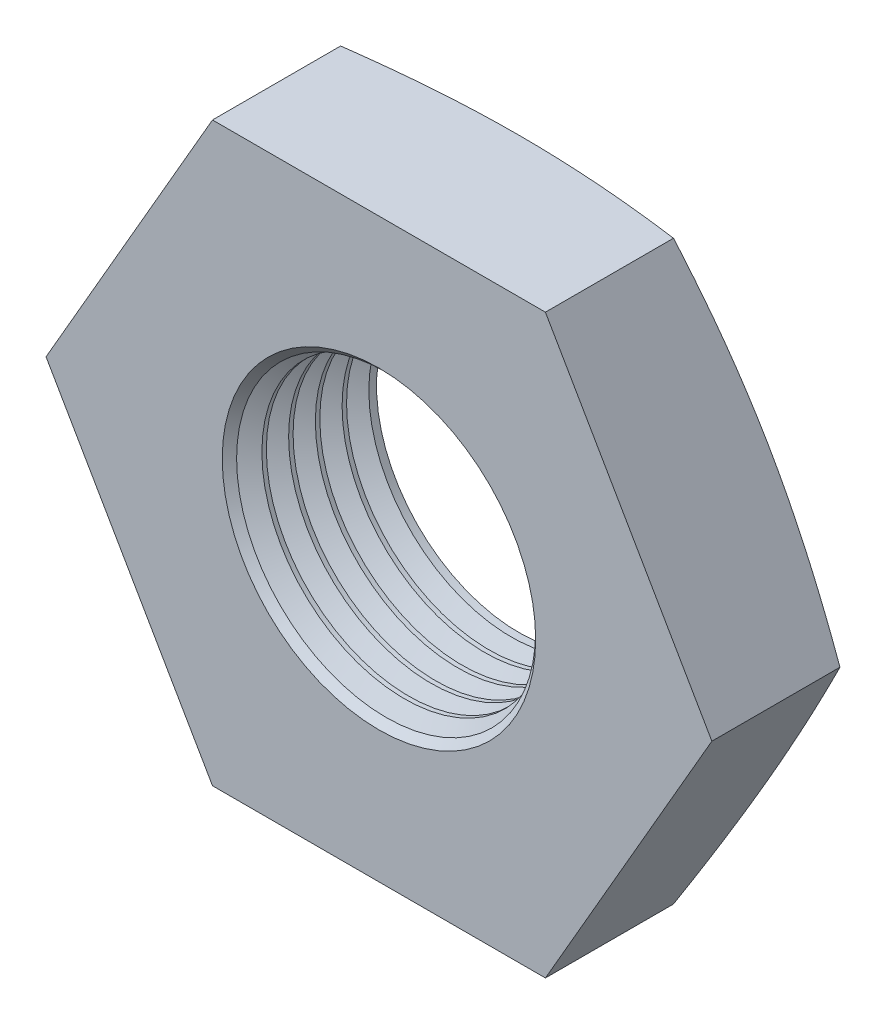
SolidWorks part; units mm, degrees
ref_plane "Front" through (0, 0, 0) normal (0, 0, 1) x (1, 0, 0)
ref_plane "Top" through (0, 0, 0) normal (0, 1, 0) x (1, 0, 0)
ref_plane "Right" through (0, 0, 0) normal (1, 0, 0) x (0, 0, -1)
sketch "Sketch1" plane through (0, 0, 0) normal (0, 0, 1) x (1, 0, 0)
  line L1 (2.0207, -3.5) -> (4.0415, 0)
  line L2 (4.0415, 0) -> (2.0207, 3.5)
  line L3 (2.0207, 3.5) -> (-2.0207, 3.5)
  line L4 (-2.0207, 3.5) -> (-4.0415, 0)
  line L5 (-4.0415, 0) -> (-2.0207, -3.5)
  line L6 (-2.0207, -3.5) -> (2.0207, -3.5)
  circle A0 centre (0, 0) radius 3.5 construction
  circle A1 centre (0, 0) radius 1.7295
  dimension "D" = 3.459
  dimension "s" = 7
  dimension "e" = 8.0829
extrude "BaseNut" add sketch "Sketch1" against normal blind 1.7
cosmetic thread "ThreadCosmetic1" [suppressed] parameters "D2"=4
sketch "Sketch2" plane through (0, 0, 0) normal (0, 1, 0) x (1, 0, 0)
  line L0 (-4.0415, 1.7) -> (-3.5, 1.7)
  line L2 (-3.5, 1.7) -> (-4.0415, 1.5549)
  line L3 (-4.0415, 1.5549) -> (-4.0415, 1.7)
  line L4 (0, 3.3759) -> (0, -9.8171) construction
  line L6 (-9.7712, 0.85) -> (9.8853, 0.85) construction
  dimension "dw" = 7
  dimension "Angle" = 15
  dimension "D2" = 0.85
revolve "Double-Chamfer" cut sketch "Sketch2" angle 360 about L4
chamfer "Chamfer1" distance 0.1729 angle 45 1 edges at (1.7295, 0, 0)
sketch "Sketch3" plane through (0, 0, 0) normal (0, 1, 0) x (1, 0, 0)
  line L0 (0, 2.7394) -> (0, -0.894) construction
  line L1 (1.459, 0.3082) -> (1.7295, 0.3082)
  line L2 (1.7295, 0.3082) -> (1.9638, 0.1729)
  line L3 (1.9638, 0.1729) -> (1.7295, 0.0377)
  line L4 (1.7295, 0.0377) -> (1.459, 0.0377)
  line L5 (1.459, 0.0377) -> (1.459, 0.3082)
  line L6 (1.7295, 0.1729) -> (-1.7295, 0.1729) construction
  dimension "D1" = 0.2705
  dimension "D2" = 3.459
revolve "Cut-Revolve10" cut sketch "Sketch3" angle 360 about L0
pattern_linear "LPattern10" count 5 spacing 0.3246 along (0, 0, -1) of "Cut-Revolve10"
equation "\"dw@Sketch2\" = \"s@Sketch1\""
equation "\"D2@Sketch2\" = \"m@BaseNut\" / 2"
equation "\"D1@Chamfer1\" = \"D@Sketch1\" / 20"
equation "\"D2@Sketch3\" = \"D@Sketch1\""
equation "\"D1@Sketch3\" = (  \"D2@ThreadCosmetic1\" - \"D@Sketch1\" )  / 2"
equation "\"D3@LPattern10\" = \"D1@Sketch3\" * 1.2"
equation "\"D1@LPattern10\" = (  \"m@BaseNut\"  - \"D1@Chamfer1\")  / \"D3@LPattern10\""
